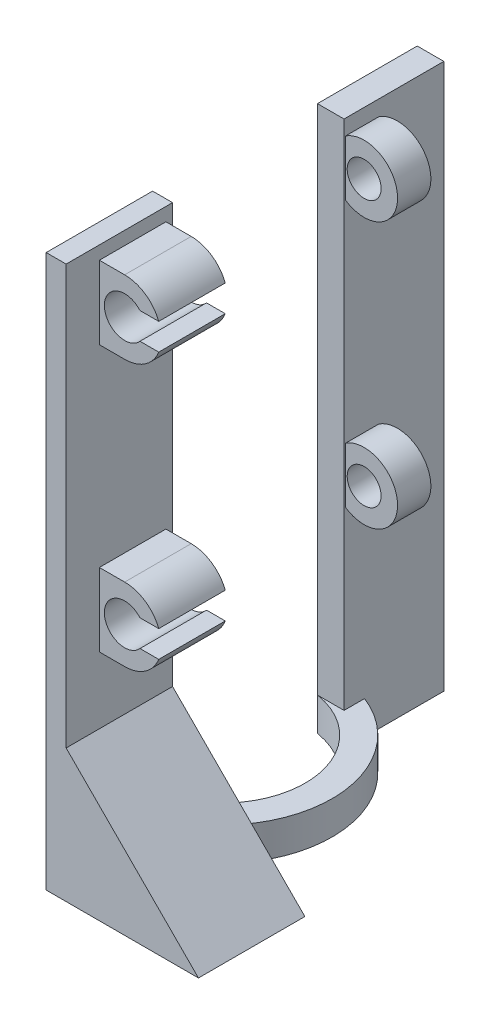
SolidWorks part; units mm, degrees
ref_plane "Front Plane" through (0, 0, 0) normal (0, 0, 1) x (1, 0, 0)
ref_plane "Top Plane" through (0, 0, 0) normal (0, 1, 0) x (1, 0, 0)
ref_plane "Right Plane" through (0, 0, 0) normal (1, 0, 0) x (0, 0, -1)
sketch "Sketch1" plane through (0, 0, 0) normal (0, 0, 1) x (1, 0, 0)
  line L0 (0, 5.5) -> (-3.7992, 5.5)
  line L1 (-3.7992, 5.5) -> (-3.7992, -5.5)
  line L2 (-3.7992, -5.5) -> (0, -5.5)
  line L3 (-20.8389, -20) -> (24.3467, -20) construction
  line L4 (2.3027, 2) -> (5.1235, 2)
  line L5 (2.3027, -2) -> (5.1235, -2)
  line L6 (2.3027, -38) -> (5.1235, -38)
  line L7 (2.3027, -42) -> (5.1235, -42)
  line L8 (-3.7992, -34.5) -> (0, -34.5)
  line L9 (-3.7992, -45.5) -> (-3.7992, -34.5)
  line L10 (0, -45.5) -> (-3.7992, -45.5)
  arc A0 (2.3027, 2) -> (2.3027, -2) centre (0, 0) ccw
  arc A1 (0, -5.5) -> (5.1235, -2) centre (0, 0) ccw
  arc A2 (5.1235, 2) -> (0, 5.5) centre (0, 0) ccw
  arc A3 (5.1235, -42) -> (0, -45.5) centre (0, -40) cw
  arc A4 (0, -34.5) -> (5.1235, -38) centre (0, -40) cw
  arc A5 (2.3027, -42) -> (2.3027, -38) centre (0, -40) cw
  dimension "D1" = 6.1
  dimension "D2" = 11
  dimension "D3" = 20
  dimension "D4" = 2
  dimension "D5" = 2
extrude "Boss-Extrude1" add sketch "Sketch1" along normal blind 10
sketch "Sketch2" plane through (-3.7992, 0, 0) normal (-1, 0, 0) x (0, 0, 1)
  line L0 (0, 5.5) -> (0, -5.5) construction
  line L1 (-1, 7.5) -> (15, 7.5)
  line L2 (-1, 7.5) -> (-1, -55.5)
  line L3 (-1, -55.5) -> (15, -55.5)
  line L4 (15, 7.5) -> (15, -55.5)
  line L5 (10, 5.5) -> (10, -5.5) construction
  line L6 (10, 5.5) -> (0, 5.5) construction
  line L7 (10, -45.5) -> (0, -45.5) construction
  dimension "D1" = 1
  dimension "D2" = 5
  dimension "D3" = 2
  dimension "D4" = 10
extrude "Boss-Extrude2" add sketch "Sketch2" along normal blind 3
ref_plane "Plane1" through (0, -75.5, 0) normal (0, -1, 0) x (-1, 0, 0)
sketch "Sketch3" plane through (0, -75.5, 0) normal (0, -1, 0) x (-1, 0, 0)
  line L1 (6.7992, 1) -> (-16.0943, 1)
  line L2 (6.7992, 1) -> (6.7992, -15)
  line L3 (6.7992, -15) -> (-16.0943, -15)
  line L4 (-16.0943, 1) -> (-16.0943, -15)
loft "Loft1" add profiles "Sketch3" section face at (-5.2992, -55.5, 7) section "Sketch3"
sketch "Sketch4" plane through (0, -75.5, 0) normal (0, -1, 0) x (1, 0, 0)
  line L0 (-6.7992, 15) -> (-6.7992, -1) construction
  line L2 (-6.7992, 3.0814) -> (-6.7992, -1)
  line L3 (-6.7992, -25.7792) -> (-6.7992, -29.8606)
  arc A0 (-6.7992, -25.7792) -> (-6.7992, -1) centre (-8.7992, -13.3896) ccw
  arc A1 (-6.7992, -29.8606) -> (-6.7992, 3.0814) centre (-8.7992, -13.3896) ccw
  point P1 (0, 0)
  dimension "D1" = 25.1
  dimension "D2" = 2
extrude "Boss-Extrude3" add sketch "Sketch4" against normal blind 5 separate body
sketch "Sketch5" plane through (0, -75.5, 0) normal (0, -1, 0) x (1, 0, 0)
  line L1 (-6.7992, -25.7792) -> (-2.7992, -25.7792)
  line L2 (-6.7992, -25.7792) -> (-6.7992, -40.7792)
  line L3 (-6.7992, -40.7792) -> (-2.7992, -40.7792)
  line L4 (-2.7992, -25.7792) -> (-2.7992, -40.7792)
  dimension "D1" = 4
  dimension "D2" = 15
extrude "Boss-Extrude4" add sketch "Sketch5" against normal blind 82
sketch "Sketch6" plane through (0, 0, 0) normal (0, 0, -1) x (-1, 0, 0)
  circle A0 centre (0, 0) radius 2.55
  dimension "D1" = 5.1
sketch "Sketch7" plane through (0, 0, 0) normal (0, 0, -1) x (-1, 0, 0)
  circle A0 centre (0, 0) radius 5.0297
extrude "Boss-Extrude5" add sketch "Sketch7" along normal blind 5 from offset 26 separate body
extrude "Cut-Extrude1" cut sketch "Sketch6" along normal blind 30
sketch "Sketch8" plane through (0, 0, -30) normal (0, 0, 1) x (1, 0, 0)
  circle A0 centre (-1.5, 0) radius 1
  circle A1 centre (1.5, 0) radius 1
  dimension "D1" = 2
  dimension "D2" = 2
  dimension "D3" = 1.5
  dimension "D4" = 1.5
extrude "Cut-Extrude2" cut sketch "Sketch8" against normal up to surface (1 mm away) up to face at (-5.0297, 0, -31)
pattern_linear "LPattern1" count 2 spacing 40 along (0, -1, 0) of "Boss-Extrude5"
equation "\"D5@Sketch1\"=\"D4@Sketch1\""
equation "\"D2@Sketch8\"=\"D1@Sketch8\""
equation "\"D4@Sketch8\"=\"D3@Sketch8\""
